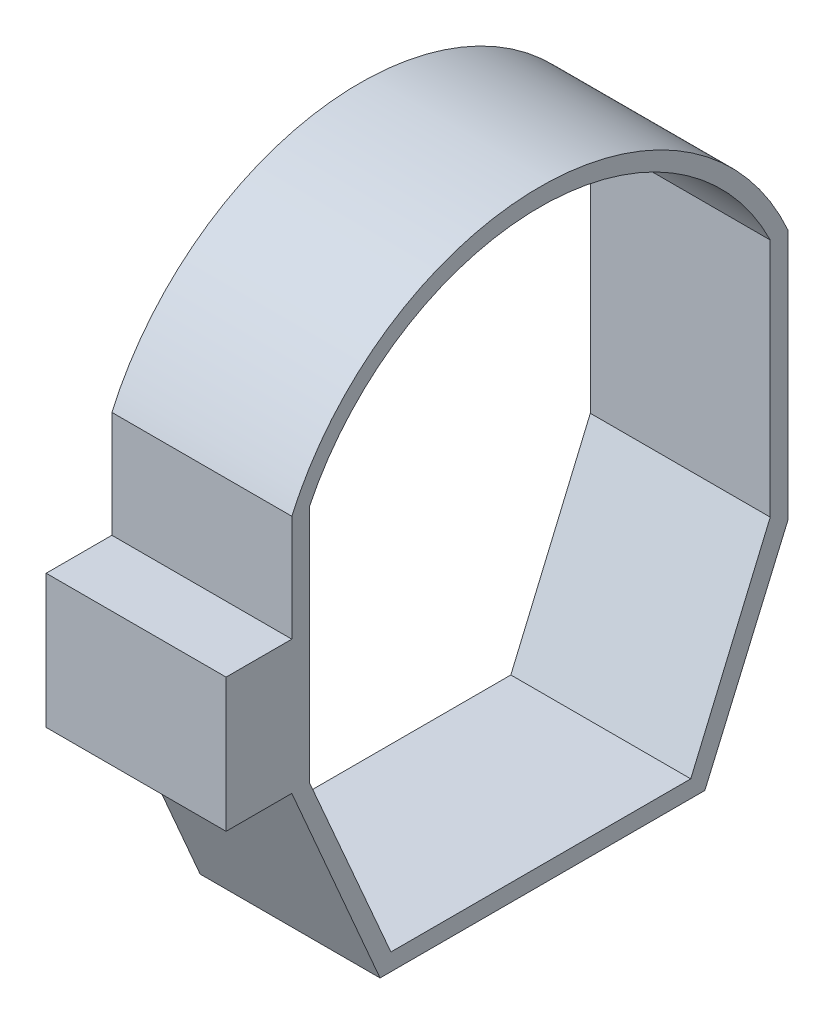
SolidWorks part; units mm, degrees
material "Nylon 6/10"
ref_plane "Front Plane" through (0, 0, 0) normal (0, 0, 1) x (1, 0, 0)
ref_plane "Top Plane" through (0, 0, 0) normal (0, 1, 0) x (1, 0, 0)
ref_plane "Right Plane" through (0, 0, 0) normal (1, 0, 0) x (0, 0, -1)
sketch3d "3DSketch1"
  line L0 (-2.3292, 18.601, 10.5842) -> (-2.3292, 8.4368, 10.5842)
  line L2 (-2.3292, 18.601, -8.923) -> (-2.3292, 8.4368, -8.923)
  line L6 (-2.3292, 8.4368, 10.5842) -> (-2.3292, 0.5216, 7.1427)
  line L8 (-2.3292, 0.5216, 7.1427) -> (-2.3292, 0.5216, -5.5573)
  line L10 (-2.3292, 0.5216, -5.5573) -> (-2.3292, 8.4368, -8.923)
  line L11 (-2.3292, 18.601, 11.339) -> (-2.3292, 8.4368, 11.339)
  line L12 (-2.3292, 8.4368, 11.339) -> (-2.3292, -0.2038, 7.601)
  line L13 (-2.3292, -0.2038, 7.601) -> (-2.3292, -0.2038, -5.5573)
  line L14 (-2.3292, -0.2038, -6.1547) -> (-2.3292, 7.945, -9.6684)
  line L15 (-2.3292, 7.945, -9.6684) -> (-2.3292, 18.601, -9.6684)
  arc A0 (-2.3292, 18.601, -8.923) -> (-2.3292, 18.601, 10.5842) centre (-2.3292, 13.8388, 0.8306) cw
  arc A1 (-2.3292, 18.601, -9.6684) -> (-2.3292, 18.601, 11.339) centre (-2.3292, 13.9383, 0.8353) cw
  point P19 (8.5249, 13.8388, 0.8306)
  point P28 (9.163, 13.9383, 0.8353)
ref_plane "Plane1" through (-2.3292, 0, 0) normal (1, 0, 0) x (0, 0, -1)
sketch "Sketch2" plane through (-2.3292, 0, 0) normal (1, 0, 0) x (0, 0, -1)
  line L0 (8.923, 18.601) -> (8.923, 8.4368)
  line L1 (8.923, 8.4368) -> (5.5573, 0.5216)
  line L2 (5.5573, 0.5216) -> (-7.1427, 0.5216)
  line L3 (-7.1427, 0.5216) -> (-10.5842, 8.4368)
  line L4 (-10.5842, 8.4368) -> (-10.5842, 18.601)
  line L5 (-11.339, 18.601) -> (-11.339, 8.4368)
  line L6 (-11.339, 18.601) -> (-11.339, 8.4368) construction
  line L7 (-11.339, 8.4368) -> (-7.601, -0.2038)
  line L8 (-11.339, 8.4368) -> (-7.601, -0.2038) construction
  line L9 (-7.601, -0.2038) -> (6.1547, -0.2038)
  line L10 (6.1547, -0.2038) -> (9.6684, 7.945)
  line L11 (9.6684, 7.945) -> (9.6684, 18.601)
  arc A0 (8.923, 18.601) -> (-10.5842, 18.601) centre (-0.8306, 13.8388) ccw
  arc A1 (9.6684, 18.601) -> (-11.339, 18.601) centre (-0.8353, 13.9383) ccw
extrude "Boss-Extrude1" add sketch "Sketch2" along normal blind 3.81 and the other way blind 3.81
sketch "Sketch3" plane through (1.4808, 0, 0) normal (1, 0, 0) x (0, 0, -1)
  line L1 (-11.339, 8.4368) -> (-14.1223, 8.4368)
  line L2 (-11.339, 8.4368) -> (-11.339, 14.0929)
  line L3 (-11.339, 14.0929) -> (-14.1223, 14.0929)
  line L4 (-14.1223, 8.4368) -> (-14.1223, 14.0929)
extrude "Boss-Extrude2" add sketch "Sketch3" against normal up to vertex (7.62 mm away)
